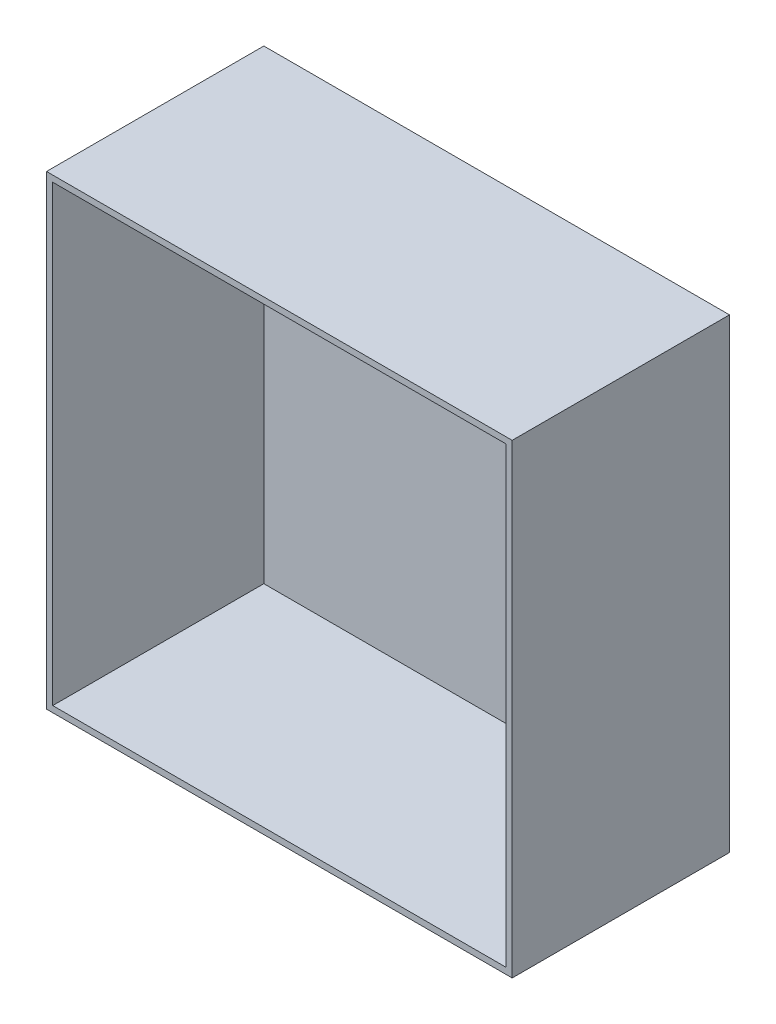
SolidWorks part; units mm, degrees
ref_plane "Ebene vorne" through (0, 0, 0) normal (0, 0, 1) x (1, 0, 0)
ref_plane "Ebene oben" through (0, 0, 0) normal (0, 1, 0) x (1, 0, 0)
ref_plane "Ebene rechts" through (0, 0, 0) normal (1, 0, 0) x (0, 0, -1)
sketch "Skizze1" plane through (0, 0, 0) normal (0, 0, 1) x (1, 0, 0)
  line L1 (0, 0) -> (150, 0)
  line L2 (0, 0) -> (0, -150)
  line L3 (0, -150) -> (150, -150)
  line L4 (150, 0) -> (150, -150)
  dimension "D1" = 150
  dimension "D2" = 150
extrude "Aufsatz-Linear austragen1" add sketch "Skizze1" along normal blind 70
sketch "Skizze2" plane through (0, 0, 70) normal (0, 0, 1) x (1, 0, 0)
  line L0 (150, 0) -> (0, 0) construction
  line L1 (2, -2) -> (148, -2)
  line L2 (2, -2) -> (2, -148)
  line L3 (2, -148) -> (148, -148)
  line L4 (148, -2) -> (148, -148)
  line L5 (0, 0) -> (0, -150) construction
  line L6 (150, -150) -> (150, 0) construction
  line L7 (0, -150) -> (150, -150) construction
  dimension "D1" = 2
  dimension "D2" = 2
  dimension "D3" = 2
  dimension "D4" = 2
extrude "Schnitt-Linear austragen1" cut sketch "Skizze2" against normal blind 68
